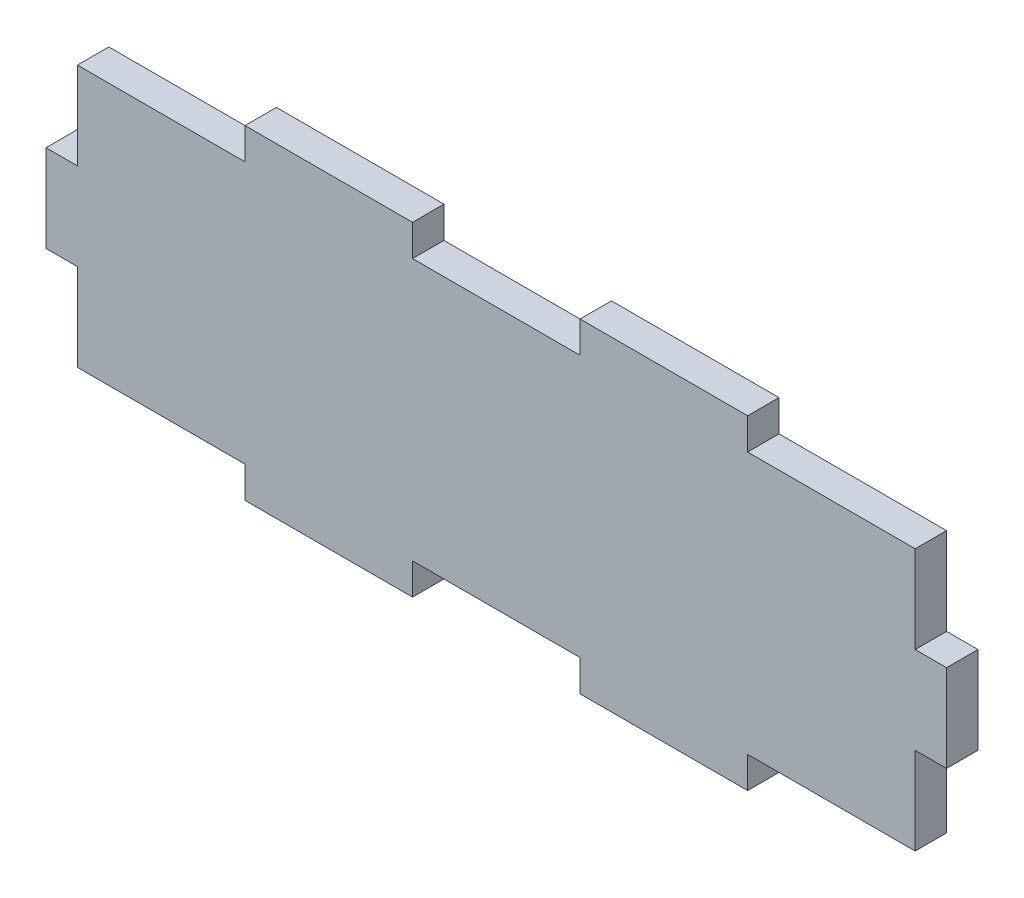
SolidWorks part; units mm, degrees
ref_plane "Front Plane" through (0, 0, 0) normal (0, 0, 1) x (1, 0, 0)
ref_plane "Top Plane" through (0, 0, 0) normal (0, 1, 0) x (1, 0, 0)
ref_plane "Right Plane" through (0, 0, 0) normal (1, 0, 0) x (0, 0, -1)
sketch "Front and Back" plane through (0, 0, 0) normal (0, 0, 1) x (1, 0, 0)
  line L0 (32, 25) -> (48, 25)
  line L1 (0, 0) -> (16, 0)
  line L2 (0, 0) -> (0, 8.3333)
  line L3 (0, 25) -> (16, 25)
  line L4 (80, 0) -> (80, 8.3333)
  line L5 (64, 25) -> (80, 25)
  line L6 (16, 25) -> (16, 28)
  line L7 (16, 28) -> (32, 28)
  line L8 (32, 25) -> (32, 28)
  line L10 (48, 25) -> (48, 28)
  line L11 (48, 28) -> (64, 28)
  line L12 (64, 25) -> (64, 28)
  line L13 (0, 16.6667) -> (-3, 16.6667)
  line L14 (80, 16.6667) -> (83, 16.6667)
  line L15 (0, 8.3333) -> (-3, 8.3333)
  line L16 (-3, 16.6667) -> (-3, 8.3333)
  line L17 (83, 16.6667) -> (83, 8.3333)
  line L18 (64, 0) -> (64, -3)
  line L19 (48, -3) -> (64, -3)
  line L20 (48, 0) -> (48, -3)
  line L21 (32, 0) -> (32, -3)
  line L22 (16, -3) -> (32, -3)
  line L23 (16, 0) -> (16, -3)
  line L24 (32, 0) -> (48, 0)
  line L25 (64, 0) -> (80, 0)
  line L26 (0, 16.6667) -> (0, 25)
  line L27 (80, 8.3333) -> (83, 8.3333)
  line L28 (80, 16.6667) -> (80, 25)
  dimension "D1" = 80
  dimension "D2" = 25
  dimension "D3" = 16
  dimension "D4" = 3
  dimension "D5" = 16
  dimension "D6" = 3
  dimension "D7" = 16
  dimension "D8" = 16
  dimension "D9" = 8.3333
  dimension "D10" = 3
  dimension "D11" = 8.3333
extrude "Front and Back Extruded" add sketch "Front and Back" along normal blind 3
